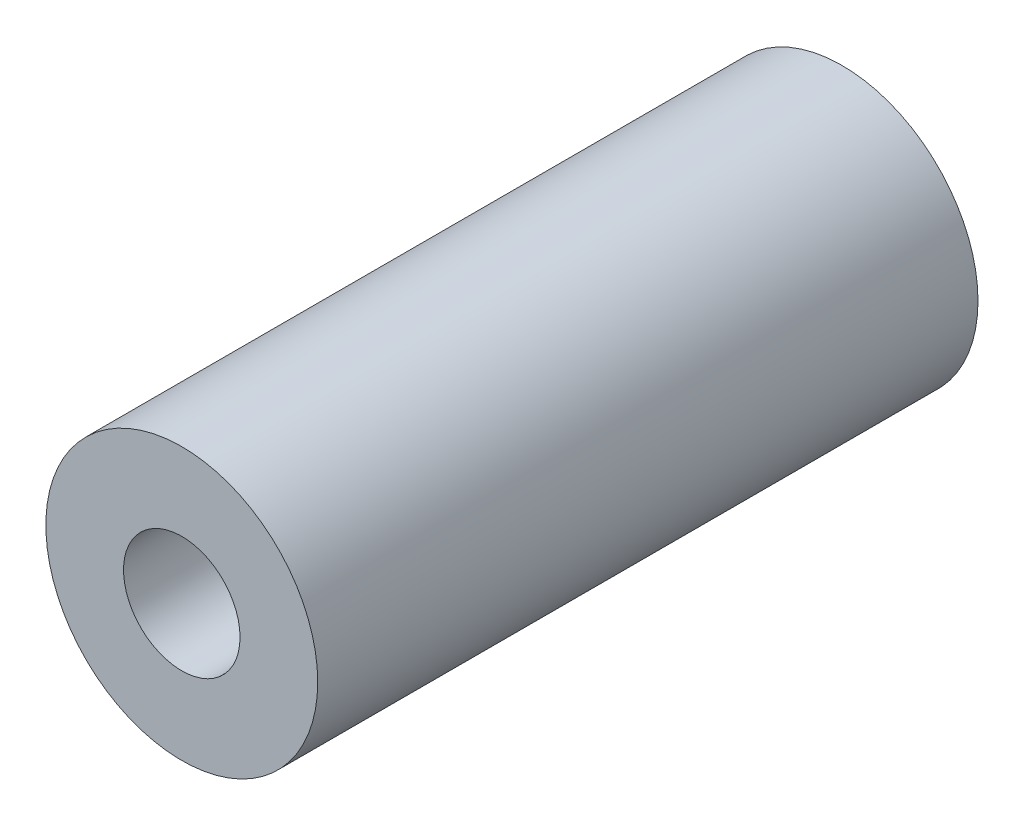
SolidWorks part; units mm, degrees
ref_plane "Front Plane" through (0, 0, 0) normal (0, 0, 1) x (1, 0, 0)
ref_plane "Top Plane" through (0, 0, 0) normal (0, 1, 0) x (1, 0, 0)
ref_plane "Right Plane" through (0, 0, 0) normal (1, 0, 0) x (0, 0, -1)
sketch "Sketch2" plane through (0, 0, 0) normal (0, 0, 1) x (1, 0, 0)
  circle A0 centre (0, 0) radius 3.5
  circle A1 centre (0, 0) radius 1.5
  dimension "D1" = 3
  dimension "D2" = 7
extrude "Boss-Extrude1" add sketch "Sketch2" along normal blind 17
